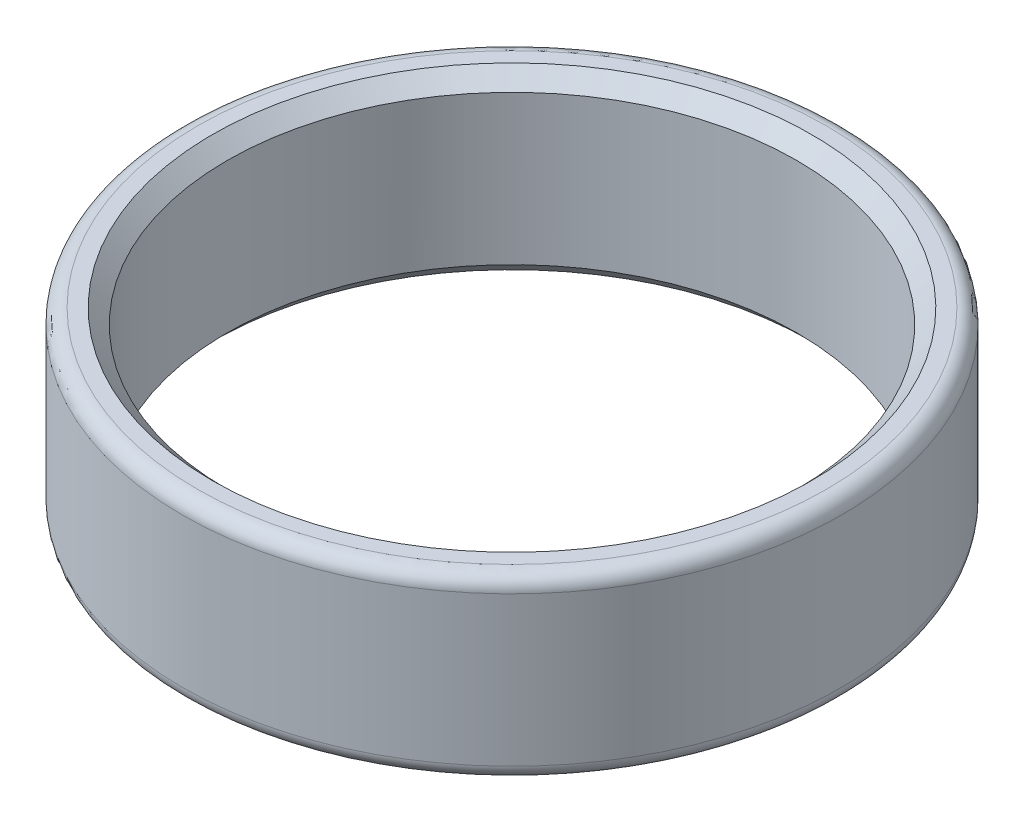
SolidWorks part; units mm, degrees
material "PET"
ref_plane "Front" through (0, 0, 0) normal (0, 0, 1) x (1, 0, 0)
ref_plane "Top" through (0, 0, 0) normal (0, 1, 0) x (1, 0, 0)
ref_plane "Right" through (0, 0, 0) normal (1, 0, 0) x (0, 0, -1)
sketch "Sketch1" plane through (0, 0, 0) normal (0, 1, 0) x (1, 0, 0)
  circle A0 centre (0, 0) radius 30.2895
  circle A1 centre (0, 0) radius 35.052
  dimension "D1" = 60.579
  dimension "D2" = 4.7625
extrude "Boss-Extrude1" add sketch "Sketch1" along normal blind 19.05
fillet "Fillet1" radius 1.5875 2 edges at (0, 0, 35.052) (0, 19.05, 35.052)
chamfer "Chamfer1" distance 1.5875 angle 45 2 edges at (0, 0, 30.2895) (0, 19.05, 30.2895)
